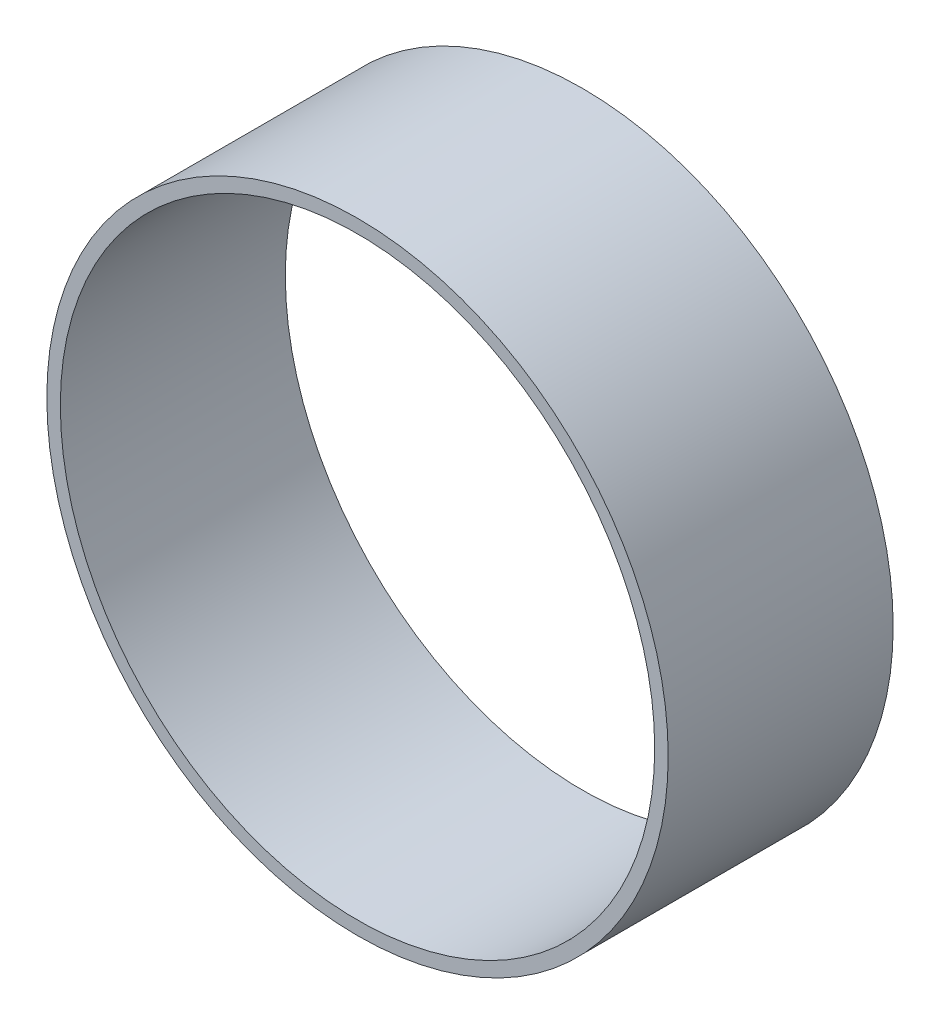
SolidWorks part; units mm, degrees
ref_plane "Спереди" through (0, 0, 0) normal (0, 0, 1) x (1, 0, 0)
ref_plane "Сверху" through (0, 0, 0) normal (0, 1, 0) x (1, 0, 0)
ref_plane "Справа" through (0, 0, 0) normal (1, 0, 0) x (0, 0, -1)
other "Configuration Table"
sketch "Эскиз1" plane through (0, 0, 0) normal (0, 0, 1) x (1, 0, 0)
  circle A0 centre (0, 0) radius 66.05
  circle A2 centre (0, 0) radius 69.05
  dimension "D1" = 132.1
  dimension "D2" = 3
extrude "Бобышка-Вытянуть1" add sketch "Эскиз1" along normal blind 50
